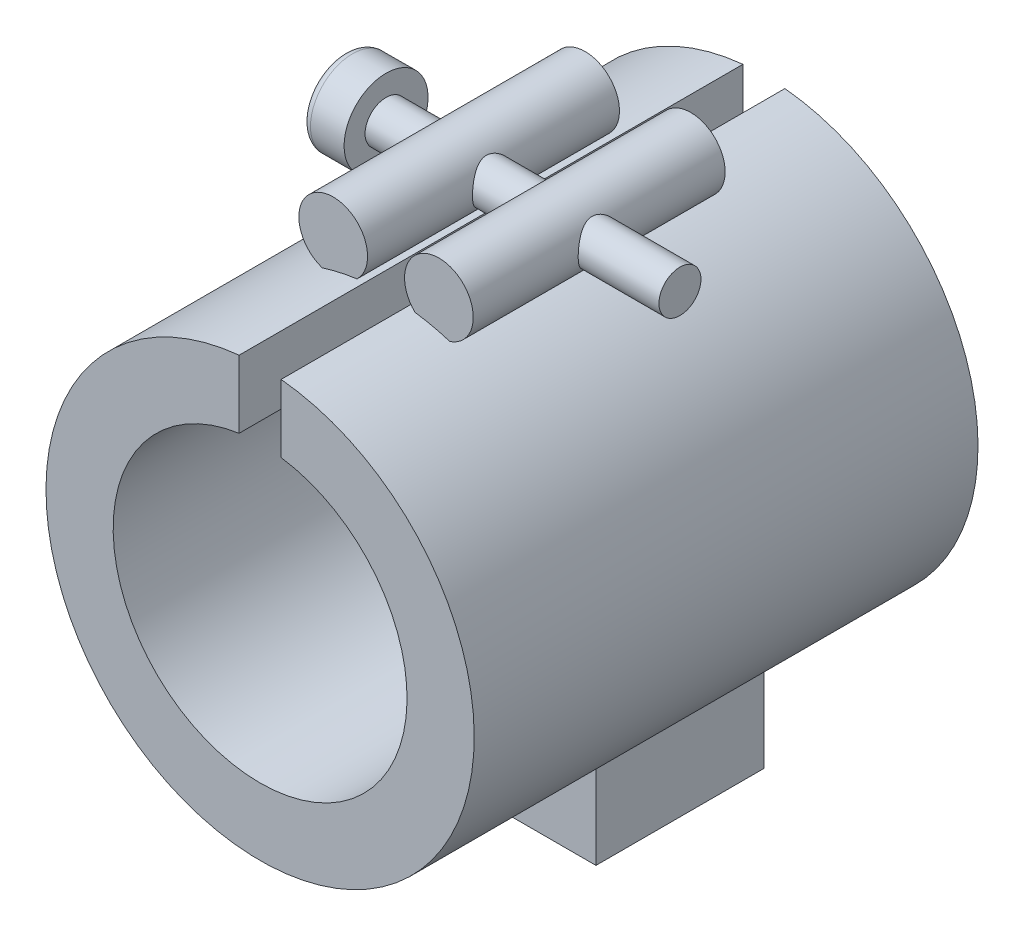
SolidWorks part; units mm, degrees
ref_plane "Front Plane" through (0, 0, 0) normal (0, 0, 1) x (1, 0, 0)
ref_plane "Top Plane" through (0, 0, 0) normal (0, 1, 0) x (1, 0, 0)
ref_plane "Right Plane" through (0, 0, 0) normal (1, 0, 0) x (0, 0, -1)
sketch "Sketch1" plane through (0, 0, 0) normal (0, 0, 1) x (1, 0, 0)
  line L0 (-2.5, 25.3772) -> (-2.5, 17.3205)
  line L1 (0, 0) -> (0, 34.2254) construction
  line L2 (2.5, 25.3772) -> (2.5, 17.3205)
  arc A0 (-2.5, 25.3772) -> (2.5, 25.3772) centre (0, 0) ccw
  arc A1 (-2.5, 17.3205) -> (2.5, 17.3205) centre (0, 0) ccw
  dimension "D1" = 35
  dimension "D2" = 8
  dimension "D3" = 5
extrude "Boss-Extrude1" add sketch "Sketch1" along normal mid plane 60
sketch "Sketch2" plane through (0, 0, 0) normal (0, 0, 1) x (1, 0, 0)
  line L0 (0, 0) -> (0, 40.0287) construction
  circle A0 centre (6.2935, 28.2115) radius 4.0912
  circle A1 centre (-6.2935, 28.2115) radius 4.0912
  arc A2 (-2.5, 25.3772) -> (2.5, 25.3772) centre (0, 0) ccw construction
  arc A3 (-2.5, 25.3772) -> (2.5, 25.3772) centre (0, 0) ccw construction
  dimension "D1" = 2.8343
  dimension "D3" = 8.1825
  dimension "D2" = 12.5871
extrude "Boss-Extrude2" add sketch "Sketch2" along normal mid plane 30
sketch "Sketch3" plane through (0, 0, 0) normal (0, 0, 1) x (1, 0, 0)
  line L0 (0, 0) -> (0, -23.0171) construction
  line L1 (-10, -23.0171) -> (10, -23.0171)
  line L2 (-10, -23.0171) -> (-10, -36)
  line L3 (-10, -36) -> (10, -36)
  line L4 (10, -23.0171) -> (10, -36)
  arc A0 (-2.5, 25.3772) -> (2.5, 25.3772) centre (0, 0) ccw construction
  dimension "D2" = 36
  dimension "D1" = 20
extrude "Boss-Extrude3" add sketch "Sketch3" against normal blind 20
sketch "Sketch4" plane through (0, 0, 0) normal (0, 0, 1) x (1, 0, 0)
  circle A0 centre (0, -38.1274) radius 3.5547
sketch "Sketch5" plane through (0, 0, 0) normal (1, 0, 0) x (0, 0, -1)
  circle A0 centre (0, 28.2115) radius 2.5
  dimension "D1" = 5
extrude "Boss-Extrude5" add sketch "Sketch5" along normal blind 20 and the other way blind 20
sketch "Sketch6" plane through (-20, 0, 0) normal (-1, 0, 0) x (0, 0, 1)
  circle A0 centre (0, 28.2115) radius 5
  circle A1 centre (0, 28.2115) radius 2.5 construction
  dimension "D1" = 10
extrude "Boss-Extrude6" add sketch "Sketch6" against normal blind 5
sketch "Sketch7" plane through (-20, 0, 0) normal (-1, 0, 0) x (0, 0, 1)
  line L1 (1.5877, 25.4615) -> (3.1754, 28.2115)
  line L2 (3.1754, 28.2115) -> (1.5877, 30.9615)
  line L3 (1.5877, 30.9615) -> (-1.5877, 30.9615)
  line L4 (-1.5877, 30.9615) -> (-3.1754, 28.2115)
  line L5 (-3.1754, 28.2115) -> (-1.5877, 25.4615)
  line L6 (-1.5877, 25.4615) -> (1.5877, 25.4615)
  circle A0 centre (0, 28.2115) radius 2.75 construction
  circle A1 centre (0, 28.2115) radius 5 construction
  point P10 (0, 25.4615)
  dimension "D1" = 5.5
extrude "Cut-Extrude1" cut sketch "Sketch7" against normal blind 3
fillet "Fillet2" radius 1 1 edges at (-20, 28.2115, 5)
